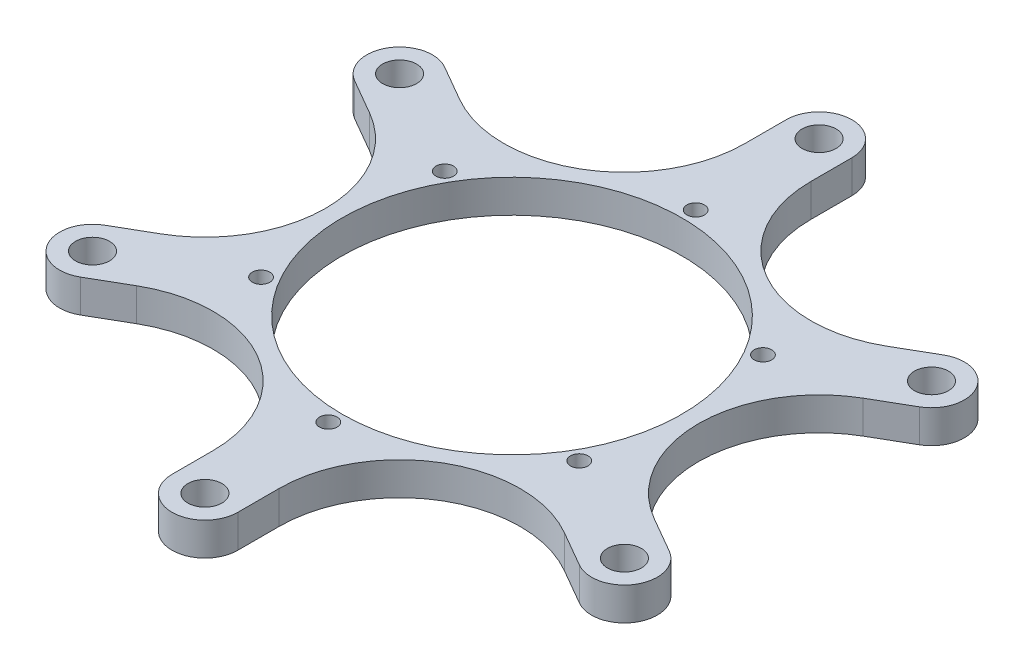
SolidWorks part; units mm, degrees
material "A-玻璃纤维"
ref_plane "前视基准面" through (0, 0, 0) normal (0, 0, 1) x (1, 0, 0)
ref_plane "上视基准面" through (0, 0, 0) normal (0, 1, 0) x (1, 0, 0)
ref_plane "右视基准面" through (0, 0, 0) normal (1, 0, 0) x (0, 0, -1)
sketch "草图1" plane through (0, 0, 0) normal (0, 1, 0) x (1, 0, 0)
  line L0 (0, 0) -> (0, 56) construction
  line L1 (28, 48.4974) -> (0, 0) construction
  line L2 (0, 56) -> (28, 48.4974) construction
  line L3 (28, 48.4974) -> (57.7613, 40.5229) construction
  line L4 (57.7613, 40.5229) -> (49.4925, 26.201) construction
  line L6 (0, 56) -> (0, 72.4956) construction
  line L7 (28, 48.4974) -> (38.75, 67.117) construction
  line L8 (38.75, 67.117) -> (41.25, 71.4471) construction
  line L9 (17, 29.4449) -> (15.5, 26.8468) construction
  line L21 (6, 56) -> (6, 48.4974)
  line L22 (45.4974, 33.1962) -> (39, 29.4449)
  line L23 (51.4974, 22.8038) -> (45, 19.0526)
  line L24 (51.4974, -22.8038) -> (45, -19.0526)
  line L25 (45.4974, -33.1962) -> (39, -29.4449)
  line L26 (6, -56) -> (6, -48.4974)
  line L27 (-6, -56) -> (-6, -48.4974)
  line L28 (-45.4974, -33.1962) -> (-39, -29.4449)
  line L29 (-51.4974, -22.8038) -> (-45, -19.0526)
  line L30 (-51.4974, 22.8038) -> (-45, 19.0526)
  line L31 (-45.4974, 33.1962) -> (-39, 29.4449)
  line L32 (-6, 56) -> (-6, 48.4974)
  circle A0 centre (0, 0) radius 31
  circle A1 centre (56, 0) radius 21.25 construction
  circle A2 centre (0, 0) radius 56 construction
  circle A7 centre (28, 48.4974) radius 21.25 construction
  circle A8 centre (0, 56) radius 7.5 construction
  circle A10 centre (28, 48.4974) radius 21.5 construction
  circle A11 centre (41.25, 71.4471) radius 5 construction
  circle A30 centre (27.7866, -48.62) radius 21.25 construction
  circle A31 centre (0, -56) radius 7.5 construction
  arc A32 (6, 48.4974) -> (39, 29.4449) centre (28, 48.4974) ccw
  arc A34 (6, 56) -> (0, 62) centre (0, 56) ccw
  arc A35 (45.4974, 33.1962) -> (53.6936, 31) centre (48.4974, 28) cw
  arc A36 (51.4974, 22.8038) -> (53.6936, 31) centre (48.4974, 28) ccw
  arc A37 (45, 19.0526) -> (45, -19.0526) centre (56, 0) ccw
  arc A38 (51.4974, -22.8038) -> (53.6936, -31) centre (48.4974, -28) cw
  arc A39 (45.4974, -33.1962) -> (53.6936, -31) centre (48.4974, -28) ccw
  arc A40 (39, -29.4449) -> (6, -48.4974) centre (28, -48.4974) ccw
  arc A41 (6, -56) -> (0, -62) centre (0, -56) cw
  arc A42 (-6, -56) -> (0, -62) centre (0, -56) ccw
  arc A43 (-6, -48.4974) -> (-39, -29.4449) centre (-28, -48.4974) ccw
  arc A44 (-45.4974, -33.1962) -> (-53.6936, -31) centre (-48.4974, -28) cw
  arc A45 (-51.4974, -22.8038) -> (-53.6936, -31) centre (-48.4974, -28) ccw
  arc A46 (-45, -19.0526) -> (-45, 19.0526) centre (-56, 0) ccw
  arc A47 (-51.4974, 22.8038) -> (-53.6936, 31) centre (-48.4974, 28) cw
  arc A48 (-45.4974, 33.1962) -> (-53.6936, 31) centre (-48.4974, 28) ccw
  arc A49 (-39, 29.4449) -> (-6, 48.4974) centre (-28, 48.4974) ccw
  arc A50 (-6, 56) -> (0, 62) centre (0, 56) cw
  circle A51 centre (48.4974, -28) radius 7.5 construction
  point P73 (0, 0)
  point P79 (0, 0)
  dimension "D1" = 62
  dimension "D2" = 42.5
  dimension "D3" = 112
  dimension "D4" = 44
  dimension "D6" = 42.5
  dimension "D7" = 15
  dimension "D8" = 56
  dimension "D9" = 43
  dimension "D11" = 10
  dimension "D13" = 6
  dimension "D14" = 6
  dimension "D15" = 42.5
  dimension "D16" = 15
  dimension "D17" = 15
  dimension "D5" = 30
  dimension "D10" = 77.5
  dimension "D12" = 82.5
extrude "凸台-拉伸1" add sketch "草图1" along normal blind 6
sketch "草图2" plane through (0, 6, 0) normal (0, 1, 0) x (1, 0, 0)
  line L0 (0, 33.5) -> (0, 0) construction
  circle A0 centre (0, 33.5) radius 1.6
  circle A1 centre (0, 56) radius 3.1
  arc A2 (6, 56) -> (-6, 56) centre (0, 56) ccw construction
  dimension "D1" = 3.2
  dimension "D2" = 33.5
  dimension "D3" = 6.2
extrude "切除-拉伸1" cut sketch "草图2" against normal blind 6
pattern_circular "阵列(圆周)1" count 6 over 360 about axis through (0, 0, 0) along (0, 1, 0) of "切除-拉伸1"
sketch "草图3" plane through (0, 6, 0) normal (0, 1, 0) x (1, 0, 0)
  line L0 (0, -56) -> (27.5786, -47.877) construction
  circle A0 centre (0, -56) radius 7.5
  circle A1 centre (27.5786, -47.877) radius 21.25
  arc A2 (39, -29.4449) -> (6, -48.4974) centre (28, -48.4974) ccw construction
  circle A3 centre (0, 0) radius 55.252
  dimension "D1" = 15
  dimension "D2" = 42.5
